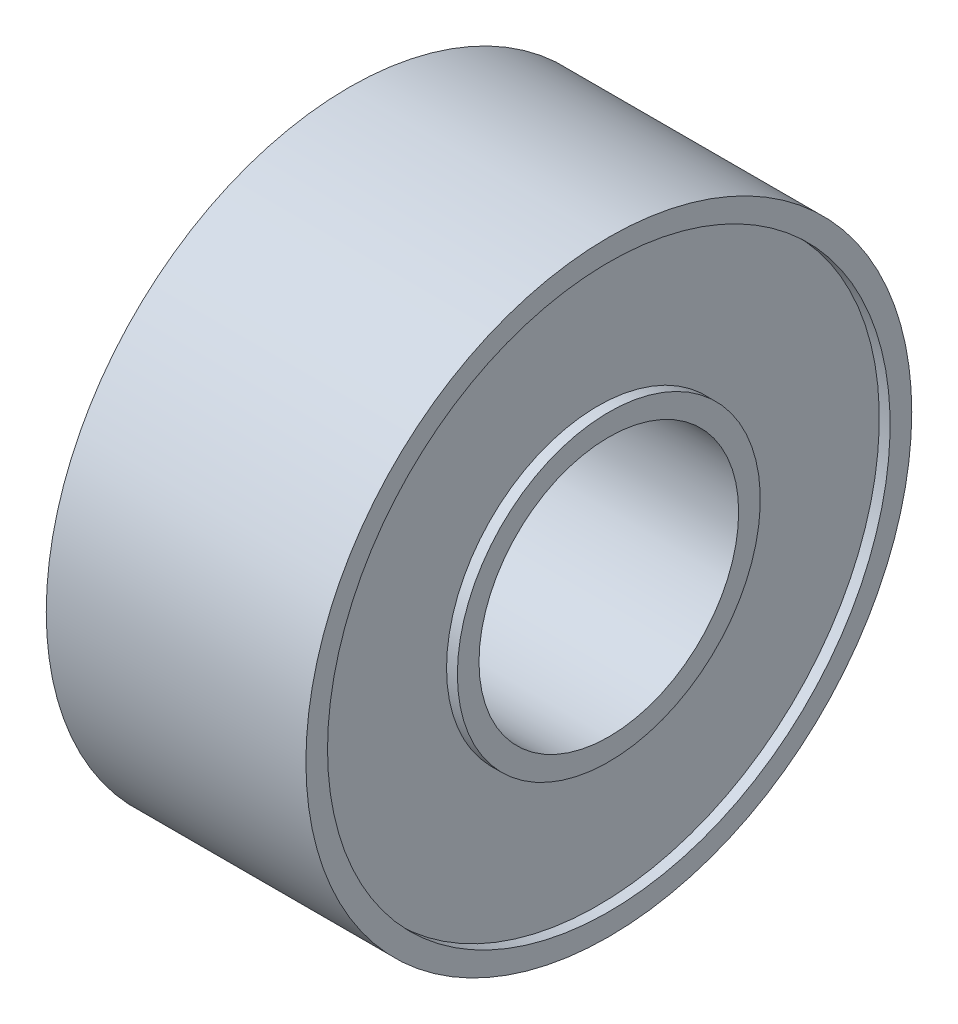
SolidWorks part; units mm, degrees
ref_plane "Front Plane" through (0, 0, 0) normal (0, 0, 1) x (1, 0, 0)
ref_plane "Top Plane" through (0, 0, 0) normal (0, 1, 0) x (1, 0, 0)
ref_plane "Right Plane" through (0, 0, 0) normal (1, 0, 0) x (0, 0, -1)
sketch "Sketch1" plane through (0, 0, 0) normal (0, 0, 1) x (1, 0, 0)
  line L0 (0, 14) -> (12, 14)
  line L1 (12, 14) -> (12, 13)
  line L2 (12, 13) -> (11.5, 13)
  line L3 (11.5, 13) -> (11.5, 7)
  line L4 (11.5, 7) -> (12, 7)
  line L5 (12, 7) -> (12, 6)
  line L6 (12, 6) -> (0, 6)
  line L7 (0, 6) -> (0, 7)
  line L8 (0, 7) -> (0.5, 7)
  line L9 (0.5, 7) -> (0.5, 13)
  line L10 (0.5, 13) -> (0, 13)
  line L11 (0, 13) -> (0, 14)
  line L12 (0, 0) -> (12.5416, 0) construction
  dimension "D1" = 14
  dimension "D2" = 6
  dimension "D3" = 12
  dimension "D4" = 7
  dimension "D5" = 13
  dimension "D6" = 0.5
revolve "Revolve1" add sketch "Sketch1" angle 360 about L12
